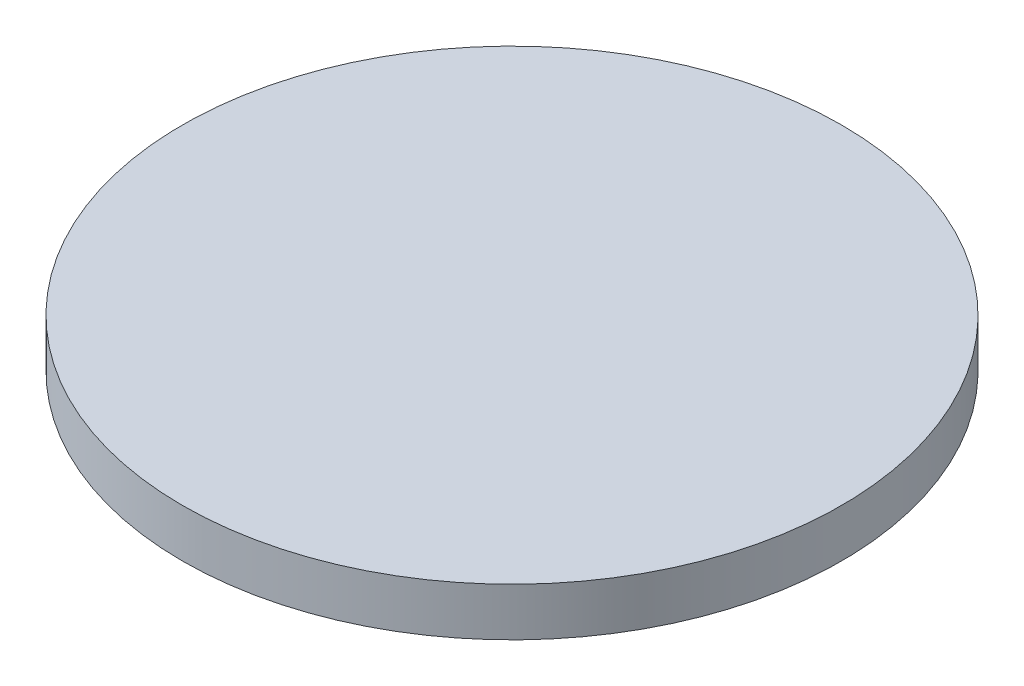
SolidWorks part; units mm, degrees
material "AISI 1020"
ref_plane "Front Plane" through (0, 0, 0) normal (0, 0, 1) x (1, 0, 0)
ref_plane "Top Plane" through (0, 0, 0) normal (0, 1, 0) x (1, 0, 0)
ref_plane "Right Plane" through (0, 0, 0) normal (1, 0, 0) x (0, 0, -1)
sketch "Sketch1" plane through (0, 0, 0) normal (0, 1, 0) x (1, 0, 0)
  circle A0 centre (0, 0) radius 68.411
extrude "Boss-Extrude1" add sketch "Sketch1" along normal blind 10
